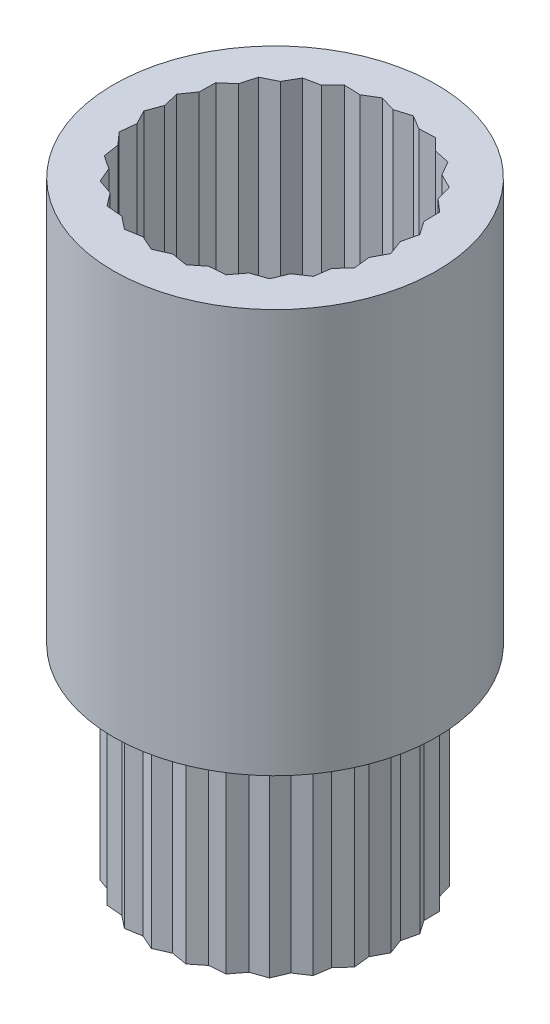
SolidWorks part; units mm, degrees
ref_plane "Front Plane" through (0, 0, 0) normal (0, 0, 1) x (1, 0, 0)
ref_plane "Top Plane" through (0, 0, 0) normal (0, 1, 0) x (1, 0, 0)
ref_plane "Right Plane" through (0, 0, 0) normal (1, 0, 0) x (0, 0, -1)
sketch "Sketch1" plane through (0, 0, 0) normal (0, 1, 0) x (1, 0, 0)
  line L0 (0, 2.925) -> (-0.3841, 3.0408)
  line L1 (-0.3841, 3.0408) -> (-0.7274, 2.8331)
  line L2 (0.3841, 3.0408) -> (0, 2.925)
  line L3 (0.7274, 2.8331) -> (0.3841, 3.0408)
  line L4 (1.1283, 2.8498) -> (0.7274, 2.8331)
  line L5 (1.4091, 2.5632) -> (1.1283, 2.8498)
  line L6 (1.8016, 2.4796) -> (1.4091, 2.5632)
  line L7 (2.0023, 2.1322) -> (1.8016, 2.4796)
  line L8 (2.3616, 1.9537) -> (2.0023, 2.1322)
  line L9 (2.4697, 1.5673) -> (2.3616, 1.9537)
  line L10 (2.7733, 1.305) -> (2.4697, 1.5673)
  line L11 (2.7818, 0.9039) -> (2.7733, 1.305)
  line L12 (3.0107, 0.5743) -> (2.7818, 0.9039)
  line L13 (2.9192, 0.1837) -> (3.0107, 0.5743)
  line L14 (3.059, -0.1925) -> (2.9192, 0.1837)
  line L15 (2.8732, -0.5481) -> (3.059, -0.1925)
  line L16 (2.915, -0.9471) -> (2.8732, -0.5481)
  line L17 (2.6466, -1.2454) -> (2.915, -0.9471)
  line L18 (2.5879, -1.6423) -> (2.6466, -1.2454)
  line L19 (2.2538, -1.8645) -> (2.5879, -1.6423)
  line L20 (2.0981, -2.2343) -> (2.2538, -1.8645)
  line L21 (1.7193, -2.3664) -> (2.0981, -2.2343)
  line L22 (1.4766, -2.6859) -> (1.7193, -2.3664)
  line L23 (1.0768, -2.7196) -> (1.4766, -2.6859)
  line L24 (0.7622, -2.9687) -> (1.0768, -2.7196)
  line L25 (0.3666, -2.9019) -> (0.7622, -2.9687)
  line L26 (0, -3.065) -> (0.3666, -2.9019)
  line L27 (-0.3666, -2.9019) -> (0, -3.065)
  line L28 (-0.7622, -2.9687) -> (-0.3666, -2.9019)
  line L29 (-1.0768, -2.7196) -> (-0.7622, -2.9687)
  line L30 (-1.4766, -2.6859) -> (-1.0768, -2.7196)
  line L31 (-1.7193, -2.3664) -> (-1.4766, -2.6859)
  line L32 (-2.0981, -2.2343) -> (-1.7193, -2.3664)
  line L33 (-2.2538, -1.8645) -> (-2.0981, -2.2343)
  line L34 (-2.5879, -1.6423) -> (-2.2538, -1.8645)
  line L35 (-2.6466, -1.2454) -> (-2.5879, -1.6423)
  line L36 (-2.915, -0.9471) -> (-2.6466, -1.2454)
  line L37 (-2.8732, -0.5481) -> (-2.915, -0.9471)
  line L38 (-3.059, -0.1925) -> (-2.8732, -0.5481)
  line L39 (-2.9192, 0.1837) -> (-3.059, -0.1925)
  line L40 (-3.0107, 0.5743) -> (-2.9192, 0.1837)
  line L41 (-2.7818, 0.9039) -> (-3.0107, 0.5743)
  line L42 (-2.7733, 1.305) -> (-2.7818, 0.9039)
  line L43 (-2.4697, 1.5673) -> (-2.7733, 1.305)
  line L44 (-2.3616, 1.9537) -> (-2.4697, 1.5673)
  line L45 (-2.0023, 2.1322) -> (-2.3616, 1.9537)
  line L46 (-1.8016, 2.4796) -> (-2.0023, 2.1322)
  line L47 (-1.4091, 2.5632) -> (-1.8016, 2.4796)
  line L48 (-1.1283, 2.8498) -> (-1.4091, 2.5632)
  line L49 (-0.7274, 2.8331) -> (-1.1283, 2.8498)
  circle A0 centre (0, 0) radius 3.065
  circle A1 centre (0, 0) radius 2.925
  point P4 (0, 2.925)
  point P7 (0.7274, 2.8331)
  point P8 (1.4091, 2.5632)
  point P9 (2.0023, 2.1322)
  point P10 (2.4697, 1.5673)
  point P11 (2.7818, 0.9039)
  point P12 (2.9192, 0.1837)
  point P13 (2.8732, -0.5481)
  point P14 (2.6466, -1.2454)
  point P15 (2.2538, -1.8645)
  point P16 (1.7193, -2.3664)
  point P17 (1.0768, -2.7196)
  point P18 (0.3666, -2.9019)
  point P19 (-0.3666, -2.9019)
  point P20 (-1.0768, -2.7196)
  point P21 (-1.7193, -2.3664)
  point P22 (-2.2538, -1.8645)
  point P23 (-2.6466, -1.2454)
  point P24 (-2.8732, -0.5481)
  point P25 (-2.9192, 0.1837)
  point P26 (-2.7818, 0.9039)
  point P27 (-2.4697, 1.5673)
  point P28 (-2.0023, 2.1322)
  point P29 (-1.4091, 2.5632)
  point P30 (-0.7274, 2.8331)
  point P31 (0, 0)
  point P107 (0, 0)
  dimension "D1" = 6.13
  dimension "D2" = 5.85
  dimension "D3" = 25
  dimension "D4" = 25
extrude "Boss-Extrude2" add sketch "Sketch1" along normal blind 5 contours A1 | A1 L37 L36 | A1 L33 L32 | A1 L35 L34 | A1 L39 L38 | A1 L41 L40 | A1 L43 L42
sketch "Sketch2" plane through (0, 5, 0) normal (0, 1, 0) x (1, 0, 0)
  circle A0 centre (0, 0) radius 4
  dimension "D1" = 8
extrude "Boss-Extrude3" add sketch "Sketch2" along normal blind 10
sketch "Sketch3" plane through (0, 15, 0) normal (0, 1, 0) x (1, 0, 0)
  line L0 (-0.7274, 2.8331) -> (-0.3841, 3.0408)
  line L1 (-0.3841, 3.0408) -> (0, 2.925)
  line L2 (0, 2.925) -> (0.3841, 3.0408)
  line L3 (0.3841, 3.0408) -> (0.7274, 2.8331)
  line L4 (0.7274, 2.8331) -> (1.1283, 2.8498)
  line L5 (1.1283, 2.8498) -> (1.4091, 2.5632)
  line L6 (1.4091, 2.5632) -> (1.8016, 2.4796)
  line L7 (1.8016, 2.4796) -> (2.0023, 2.1322)
  line L8 (2.0023, 2.1322) -> (2.3616, 1.9537)
  line L9 (2.3616, 1.9537) -> (2.4697, 1.5673)
  line L10 (2.4697, 1.5673) -> (2.7733, 1.305)
  line L11 (2.7733, 1.305) -> (2.7818, 0.9039)
  line L12 (2.7818, 0.9039) -> (3.0107, 0.5743)
  line L13 (3.0107, 0.5743) -> (2.9192, 0.1837)
  line L14 (2.9192, 0.1837) -> (3.059, -0.1925)
  line L15 (3.059, -0.1925) -> (2.8732, -0.5481)
  line L16 (2.8732, -0.5481) -> (2.915, -0.9471)
  line L17 (2.915, -0.9471) -> (2.6466, -1.2454)
  line L18 (2.6466, -1.2454) -> (2.5879, -1.6423)
  line L19 (2.5879, -1.6423) -> (2.2538, -1.8645)
  line L20 (2.2538, -1.8645) -> (2.0981, -2.2343)
  line L21 (2.0981, -2.2343) -> (1.7193, -2.3664)
  line L22 (1.7193, -2.3664) -> (1.4766, -2.6859)
  line L23 (1.4766, -2.6859) -> (1.0768, -2.7196)
  line L24 (1.0768, -2.7196) -> (0.7622, -2.9687)
  line L25 (0.7622, -2.9687) -> (0.3666, -2.9019)
  line L26 (0.3666, -2.9019) -> (0, -3.065)
  line L27 (0, -3.065) -> (-0.3666, -2.9019)
  line L28 (-0.3666, -2.9019) -> (-0.7622, -2.9687)
  line L29 (-0.7622, -2.9687) -> (-1.0768, -2.7196)
  line L30 (-1.0768, -2.7196) -> (-1.4766, -2.6859)
  line L31 (-1.4766, -2.6859) -> (-1.7193, -2.3664)
  line L32 (-1.7193, -2.3664) -> (-2.0981, -2.2343)
  line L33 (-2.0981, -2.2343) -> (-2.2538, -1.8645)
  line L34 (-2.2538, -1.8645) -> (-2.5879, -1.6423)
  line L35 (-2.5879, -1.6423) -> (-2.6466, -1.2454)
  line L36 (-2.6466, -1.2454) -> (-2.915, -0.9471)
  line L37 (-2.915, -0.9471) -> (-2.8732, -0.5481)
  line L38 (-2.8732, -0.5481) -> (-3.059, -0.1925)
  line L39 (-3.059, -0.1925) -> (-2.9192, 0.1837)
  line L40 (-2.9192, 0.1837) -> (-3.0107, 0.5743)
  line L41 (-3.0107, 0.5743) -> (-2.7818, 0.9039)
  line L42 (-2.7818, 0.9039) -> (-2.7733, 1.305)
  line L43 (-2.7733, 1.305) -> (-2.4697, 1.5673)
  line L44 (-2.4697, 1.5673) -> (-2.3616, 1.9537)
  line L45 (-2.3616, 1.9537) -> (-2.0023, 2.1322)
  line L46 (-2.0023, 2.1322) -> (-1.8016, 2.4796)
  line L47 (-1.8016, 2.4796) -> (-1.4091, 2.5632)
  line L48 (-1.4091, 2.5632) -> (-1.1283, 2.8498)
  line L49 (-1.1283, 2.8498) -> (-0.7274, 2.8331)
  point P4 (0, 2.925)
  point P7 (0.7274, 2.8331)
  point P8 (1.4091, 2.5632)
  point P9 (2.0023, 2.1322)
  point P10 (2.4697, 1.5673)
  point P11 (2.7818, 0.9039)
  point P12 (2.9192, 0.1837)
  point P13 (2.8732, -0.5481)
  point P14 (2.6466, -1.2454)
  point P15 (2.2538, -1.8645)
  point P16 (1.7193, -2.3664)
  point P17 (1.0768, -2.7196)
  point P18 (0.3666, -2.9019)
  point P19 (-0.3666, -2.9019)
  point P20 (-1.0768, -2.7196)
  point P21 (-1.7193, -2.3664)
  point P22 (-2.2538, -1.8645)
  point P23 (-2.6466, -1.2454)
  point P24 (-2.8732, -0.5481)
  point P25 (-2.9192, 0.1837)
  point P26 (-2.7818, 0.9039)
  point P27 (-2.4697, 1.5673)
  point P28 (-2.0023, 2.1322)
  point P29 (-1.4091, 2.5632)
  point P30 (-0.7274, 2.8331)
  point P31 (0, 0)
  point P107 (0, 0)
  dimension "D3" = 25
  dimension "D4" = 25
extrude "Cut-Extrude4" cut sketch "Sketch3" against normal blind 5
